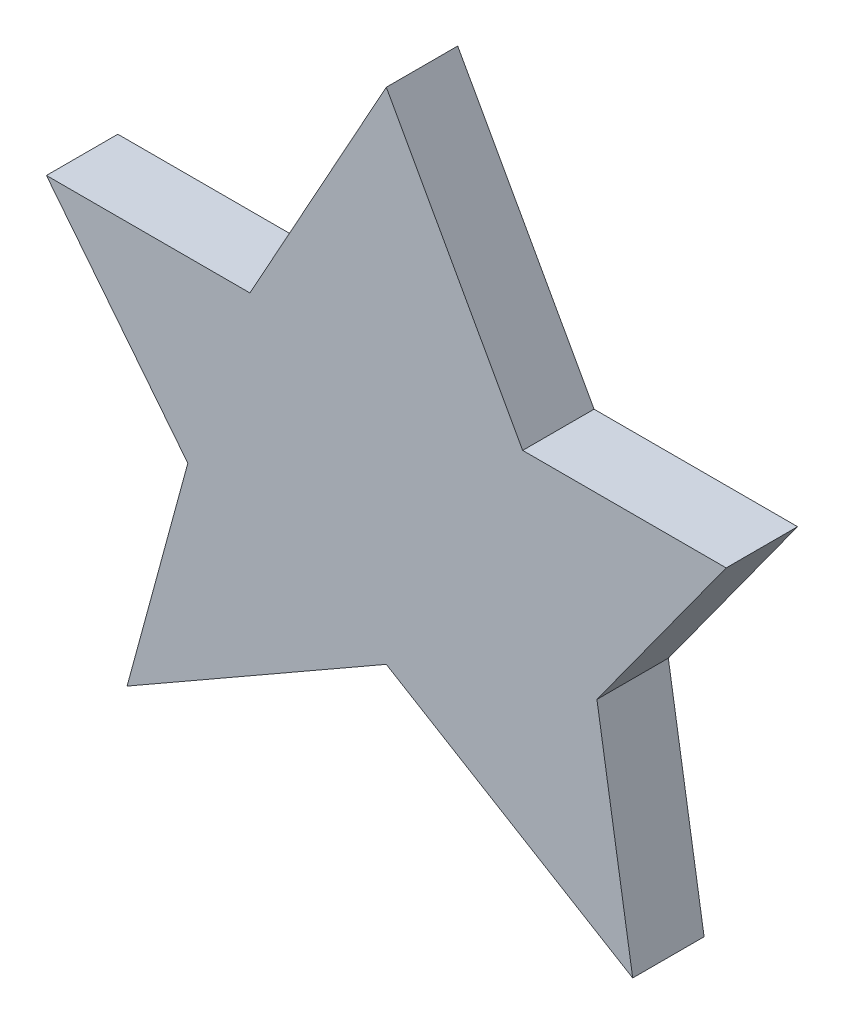
SolidWorks part; units mm, degrees
ref_plane "前视基准面" through (0, 0, 0) normal (0, 0, 1) x (1, 0, 0)
ref_plane "上视基准面" through (0, 0, 0) normal (0, 1, 0) x (1, 0, 0)
ref_plane "右视基准面" through (0, 0, 0) normal (1, 0, 0) x (0, 0, -1)
other "Configuration Table"
sketch "草图1" plane through (0, 0, 0) normal (0, 0, 1) x (1, 0, 0)
  line L0 (0, 50) -> (19.1, 15.5)
  line L1 (19.1, 15.5) -> (47.6, 15.5)
  line L2 (47.6, 15.5) -> (29.5, -9.5)
  line L3 (29.5, -9.5) -> (34.5088, -40.7868)
  line L4 (34.5088, -40.7868) -> (0, -20)
  line L5 (0, -20) -> (-36.3, -40.7868)
  line L6 (-36.3, -40.7868) -> (-27.7979, -9.5)
  line L7 (-27.7979, -9.5) -> (-47.6, 15.5)
  line L8 (-47.6, 15.5) -> (-19.1, 15.5)
  line L9 (-19.1, 15.5) -> (0, 50)
extrude "凸台-拉伸1" add sketch "草图1" along normal blind 10
